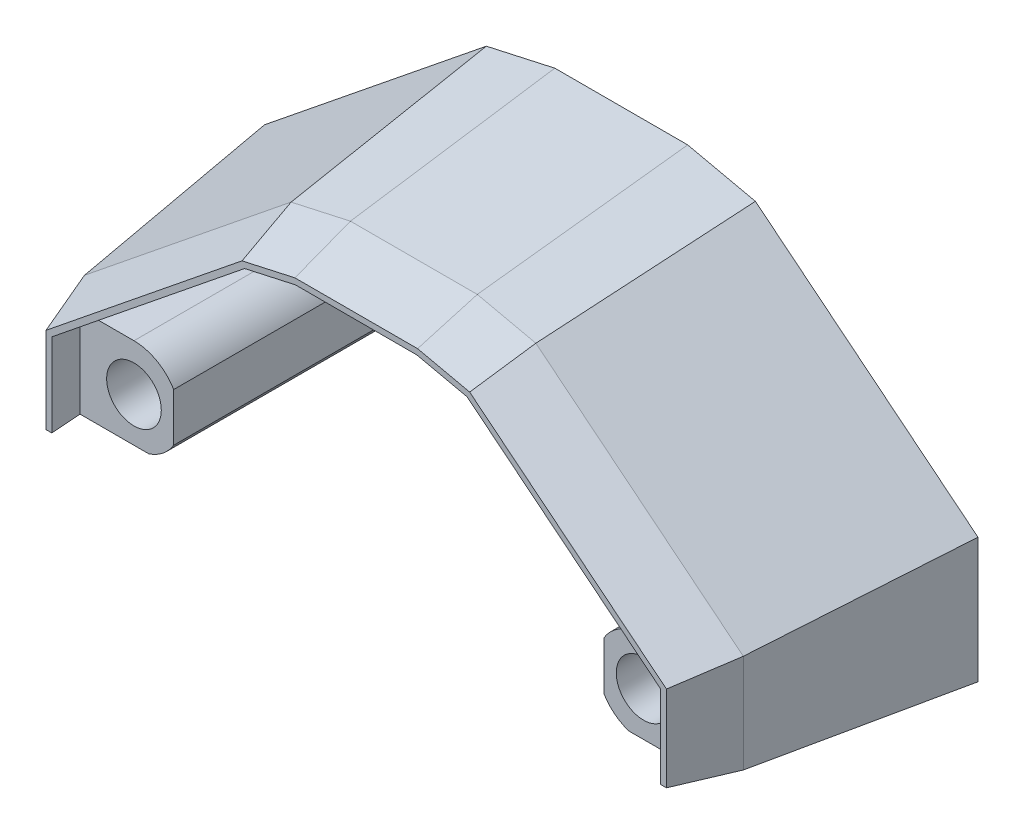
SolidWorks part; units mm, degrees
other "Marquage1"
sketch "Esquisse6" plane through (27.6879, 19.4079, 22.8) normal (0.7597, 0.6444, 0.0875) x (0.4542, -0.4295, -0.7806)
ref_plane "Plan de face" through (0, 0, 0) normal (0, 0, 1) x (1, 0, 0)
ref_plane "Plan de dessus" through (0, 0, 0) normal (0, 1, 0) x (1, 0, 0)
ref_plane "Plan de droite" through (0, 0, 0) normal (1, 0, 0) x (0, 0, -1)
sketch "Esquisse2" plane through (0, 0, 22.8) normal (0, 0, -1) x (-1, 0, 0)
  line L0 (9.6031, 16.9364) -> (5.2212, 17.9079)
  line L1 (5.2212, 17.9079) -> (-5.2212, 17.9079)
  line L2 (-5.2212, 17.9079) -> (-9.5356, 16.9513)
  line L3 (-9.5356, 16.9513) -> (-26.1879, 3.5144)
  line L4 (-26.1879, 3.5144) -> (-26.1879, -3.6055)
  line L5 (9.6031, 16.9364) -> (26.1879, 3.5539)
  line L6 (26.1879, 3.5539) -> (26.1879, -3.6055)
  line L16 (27.6879, 4.271) -> (27.6879, -3.6055)
  line L17 (10.2713, 18.3247) -> (27.6879, 4.271)
  line L18 (10.2713, 18.3247) -> (5.3855, 19.4079)
  line L19 (5.3855, 19.4079) -> (-5.3855, 19.4079)
  line L20 (-5.3855, 19.4079) -> (-10.2037, 18.3396)
  line L21 (-10.2037, 18.3396) -> (-27.6879, 4.2315)
  line L22 (-27.6879, 4.2315) -> (-27.6879, -3.6055)
  line L23 (-27.6879, -3.6055) -> (-26.1879, -3.6055)
  line L24 (26.1879, -3.6055) -> (27.6879, -3.6055)
  dimension "D1" = 1.5
sketch "Esquisse7" plane through (0, 0, 0) normal (0, 0, 1) x (1, 0, 0)
  line L16 (30.6879, -5.1055) -> (30.6879, 5.6656)
  line L17 (30.6879, 5.6656) -> (11.54, 21.1162)
  line L18 (11.54, 21.1162) -> (5.714, 22.4079)
  line L19 (5.714, 22.4079) -> (-5.714, 22.4079)
  line L20 (-5.714, 22.4079) -> (-11.6076, 21.1012)
  line L21 (-11.6076, 21.1012) -> (-30.6879, 5.7051)
  line L22 (-30.6879, 5.7051) -> (-30.6879, -5.1055)
  line L23 (-30.6879, -5.1055) -> (-29.1879, -5.1055)
  line L24 (29.1879, -5.1055) -> (30.6879, -5.1055)
  line L32 (-29.1879, 4.9881) -> (-29.1879, -5.1055)
  line L33 (-29.1879, -5.1055) -> (-24.6879, -5.1055)
  line L34 (-24.6879, -5.1055) -> (-24.6879, 2.8369)
  line L35 (-24.6879, 2.8369) -> (-8.935, 15.5481)
  line L36 (-8.935, 15.5481) -> (-5.0569, 16.4079)
  line L37 (-5.0569, 16.4079) -> (5.0569, 16.4079)
  line L38 (5.0569, 16.4079) -> (8.8674, 15.5631)
  line L39 (8.8674, 15.5631) -> (24.6879, 2.7973)
  line L40 (24.6879, 2.7973) -> (24.6879, -5.1055)
  line L41 (24.6879, -5.1055) -> (29.1879, -5.1055)
  line L42 (29.1879, -5.1055) -> (29.1879, 4.9485)
  line L43 (29.1879, 4.9485) -> (10.8719, 19.7279)
  line L44 (10.8719, 19.7279) -> (5.5498, 20.9079)
  line L45 (5.5498, 20.9079) -> (-5.5498, 20.9079)
  line L46 (-5.5498, 20.9079) -> (-10.9395, 19.7129)
  line L47 (-10.9395, 19.7129) -> (-29.1879, 4.9881)
  line L48 (-29.1879, 4.9881) -> (-29.1879, -5.1055)
  line L58 (29.1879, -5.1055) -> (29.1879, 4.9485)
  line L59 (29.1879, 4.9485) -> (10.8719, 19.7279)
  line L60 (10.8719, 19.7279) -> (5.5498, 20.9079)
  line L61 (5.5498, 20.9079) -> (-5.5498, 20.9079)
  line L62 (-5.5498, 20.9079) -> (-10.9395, 19.7129)
  line L63 (-10.9395, 19.7129) -> (-29.1879, 4.9881)
  dimension "D1" = 1.5
  dimension "D2" = 1.5
loft "Lissage2" add profiles "Esquisse2", "Esquisse7"
chamfer "Chanfrein1" distance 1 distance2 5 7 edges
sketch "Esquisse8" plane through (0, 0, 20) normal (0, 0, -1) x (-1, 0, 0)
  line L0 (0, 0) -> (0, 7.1676) construction
  line L4 (-21.92, 4) -> (-21.92, -4)
  line L5 (21.92, 4) -> (21.92, -4)
  arc A2 (-21.92, -4) -> (-21.92, 4) centre (-21.92, 0) ccw
  arc A4 (21.92, -4) -> (21.92, 4) centre (21.92, 0) cw
  circle M1 centre (21.92, 0) radius 1.25
  line M3 (23.29, 3.3075) -> (17.8043, 5.5797)
  arc M5 (16.7127, 6.6848) -> (16.7127, -6.6848) centre (0, 0) cw
  line M7 (17.8043, -5.5797) -> (23.29, -3.3075)
  dimension "D2" = 8
extrude "Boss.-Extru.5" add sketch "Esquisse8" along normal up to surface (20 mm away) separate body contours A4 L5 M7 M1 M3 M5 | L5 M1 | A4 M5 | A2 L4
sketch "Esquisse11" plane through (21.92, 0, 0) normal (1, 0, 0) x (0, 0, -1)
  line L0 (-20, -3.7897) -> (-16.8039, -4)
  line L1 (-20, 4) -> (-20, -4) construction
  line L2 (-17.8427, -3.9317) -> (-22.8, -3.6055) construction
  line L3 (-17.8427, -3.9317) -> (0, -5.1055) construction
  line L4 (0, -4) -> (-20, -4) construction
  line L5 (-16.8039, -4) -> (-20, -4)
  line L6 (-20, -4) -> (-20, -3.7897)
extrude "Enlèv. mat.-Extru.2" cut sketch "Esquisse11" against normal through all both and the other way through all
sketch "Esquisse12" plane through (21.92, 0, 0) normal (1, 0, 0) x (0, 0, -1)
  line L0 (-16.8039, -4) -> (-20, -3.7897)
  line L1 (-20, -3.7897) -> (-20, 4)
  line L2 (-20, 4) -> (-20, -3.7897) construction
  line L3 (-20, 4) -> (0, 4)
  line L4 (0, 4) -> (0, -4)
  line L5 (0, -4) -> (-16.8039, -4)
extrude "Boss.-Extru.6" add sketch "Esquisse12" along normal up to next
sketch "Esquisse14" plane through (-21.92, 0, 0) normal (-1, 0, 0) x (0, 0, 1)
  line L0 (0, 4) -> (20, 4)
  line L1 (20, 4) -> (20, -3.7897)
  line L2 (20, -3.7897) -> (16.8039, -4)
  line L3 (16.8039, -4) -> (0, -4)
  line L4 (0, -4) -> (0, 4)
  point P3 (20, 4)
extrude "Boss.-Extru.7" add sketch "Esquisse14" along normal up to next
sketch "Esquisse15" plane through (0, 0, 0) normal (0, 0, -1) x (-1, 0, 0)
  line L0 (-18.5, 2.0745) -> (-18.5, -2.0745)
  line L1 (18.5, 3.2954) -> (18.5, -3.2954)
  arc A0 (-21.92, -4) -> (-21.92, 4) centre (-21.92, 0) ccw construction
  arc A2 (-18.5, -2.0745) -> (-18.5, 2.0745) centre (-21.92, 0) ccw
  arc A3 (18.5, 3.2954) -> (18.5, -3.2954) centre (21.92, 0) ccw
  arc M4 (21.92, 4) -> (21.92, -4) centre (21.92, 0) ccw
  arc M18 (-21.92, -4) -> (-21.92, 4) centre (-21.92, 0) ccw
  dimension "D1" = 18.5
  dimension "D2" = 18.5
extrude "Enlèv. mat.-Extru.3" cut sketch "Esquisse15" against normal through all both and the other way through all contours L0 M18 | L1 M4 | L1 A3 M4
sketch "Esquisse16" plane through (0, 0, 0) normal (0, 0, -1) x (-1, 0, 0)
  circle A0 centre (-21.92, 0) radius 2.35
  circle A1 centre (21.92, 0) radius 2.35
  dimension "D1" = 4.7
  dimension "D2" = 4.7
extrude "Enlèv. mat.-Extru.4" cut sketch "Esquisse16" against normal blind 4 and the other way through all
sketch "Esquisse17" plane through (0, 0, 20) normal (0, 0, 1) x (1, 0, 0)
  circle A0 centre (-21.92, 0) radius 2.35
  circle A1 centre (21.92, 0) radius 2.35
  dimension "D1" = 4.7
  dimension "D2" = 4.7
extrude "Enlèv. mat.-Extru.5" cut sketch "Esquisse17" against normal blind 4
